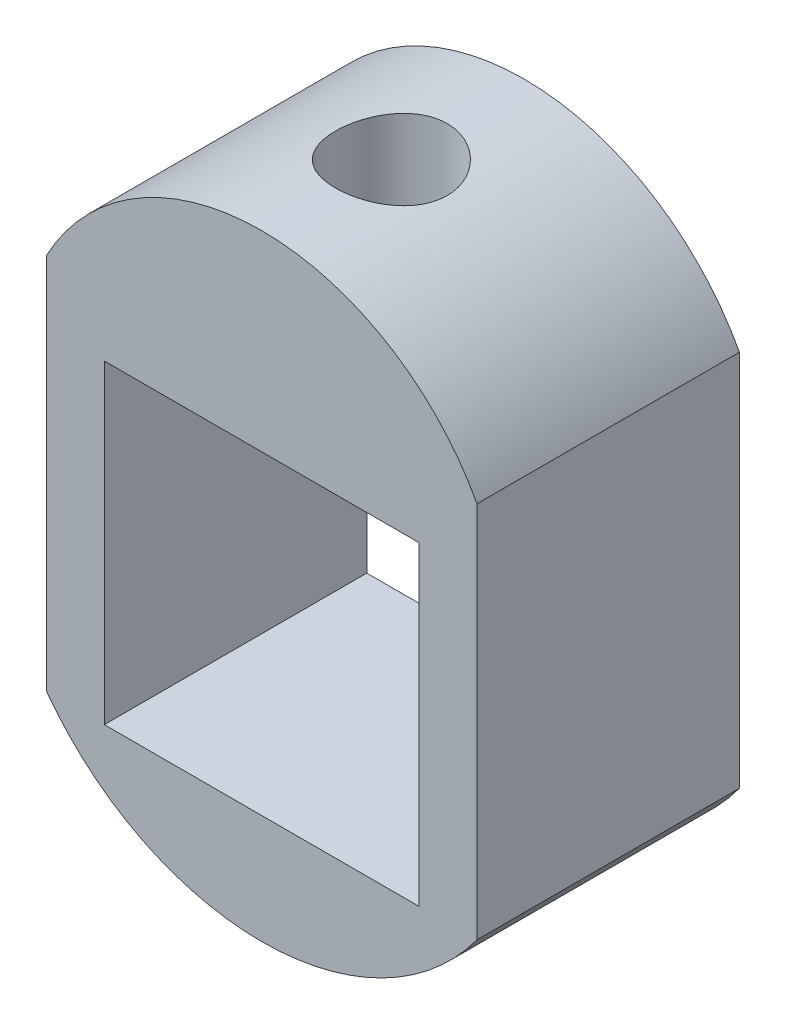
SolidWorks part; units mm, degrees
ref_plane "Front Plane" through (0, 0, 0) normal (0, 0, 1) x (1, 0, 0)
ref_plane "Top Plane" through (0, 0, 0) normal (0, 1, 0) x (1, 0, 0)
ref_plane "Right Plane" through (0, 0, 0) normal (1, 0, 0) x (0, 0, -1)
sketch "Sketch3" plane through (0, 0, 0) normal (0, 0, 1) x (1, 0, 0)
  line L0 (0, -6.35) -> (0, -8.89) construction
  line L1 (-3.81, -6.35) -> (3.81, -6.35)
  line L2 (-3.81, -6.35) -> (-3.81, 1.27)
  line L3 (-3.81, 1.27) -> (3.81, 1.27)
  line L4 (3.81, -6.35) -> (3.81, 1.27)
  line L5 (-3.81, -6.35) -> (3.81, 1.27) construction
  line L6 (-3.81, 1.27) -> (3.81, -6.35) construction
  line L7 (-5.207, 2.7861) -> (-5.207, -6.35)
  line L9 (5.207, 2.7861) -> (5.207, -6.35)
  line L10 (0, 10.9855) -> (0, -10.9855) construction
  line L11 (-5.207, -1.782) -> (5.207, -1.782) construction
  circle A0 centre (0, 0) radius 10.9855 construction
  arc A1 (-5.207, 2.7861) -> (5.207, 2.7861) centre (0, 0) cw
  arc A2 (-5.207, -6.35) -> (5.207, -6.35) centre (0, -2.54) ccw
  point P3 (0, -2.54)
  point P12 (0, 0)
  point P17 (5.207, 4.7588)
  point P20 (0, -1.782)
  point P22 (0, 5.9055)
  point P23 (5.207, 2.3215)
  dimension "D1" = 21.971
  dimension "D6" = 10.414
  dimension "D7" = 5.08
  dimension "D2" = 2.54
  dimension "D3" = 7.62
  dimension "D4" = 7.62
  dimension "D5" = 2.54
extrude "Boss-Extrude2" add sketch "Sketch3" along normal blind 6.35
ref_plane "Plane1" through (0, 5.9055, 0) normal (0, 1, 0) x (1, 0, 0)
sketch "Sketch6" plane through (0, 5.9055, 0) normal (0, 1, 0) x (1, 0, 0)
  line L0 (0, 0) -> (0, -6.4287) construction
  circle A0 centre (0, -3.2143) radius 1.3526
  point P3 (0, -3.2143)
  dimension "D1" = 2.7051
extrude "Cut-Extrude1" cut sketch "Sketch6" against normal blind 3.81
ref_plane "Plane2" through (0, -8.992, 0) normal (0, -1, 0) x (-1, 0, 0)
sketch "Sketch7" plane through (0, -8.992, 0) normal (0, -1, 0) x (-1, 0, 0)
  line L0 (0, -6.35) -> (0, 0) construction
  line L1 (-5.207, -6.35) -> (5.207, -6.35) construction
  circle A0 centre (0, -3.175) radius 1.3526
  point P3 (0, -3.175)
  point P6 (0, 0)
  point P7 (0, 0)
  point P8 (0, 0)
  dimension "D1" = 2.7051
extrude "Cut-Extrude2" cut sketch "Sketch7" against normal blind 2.54
